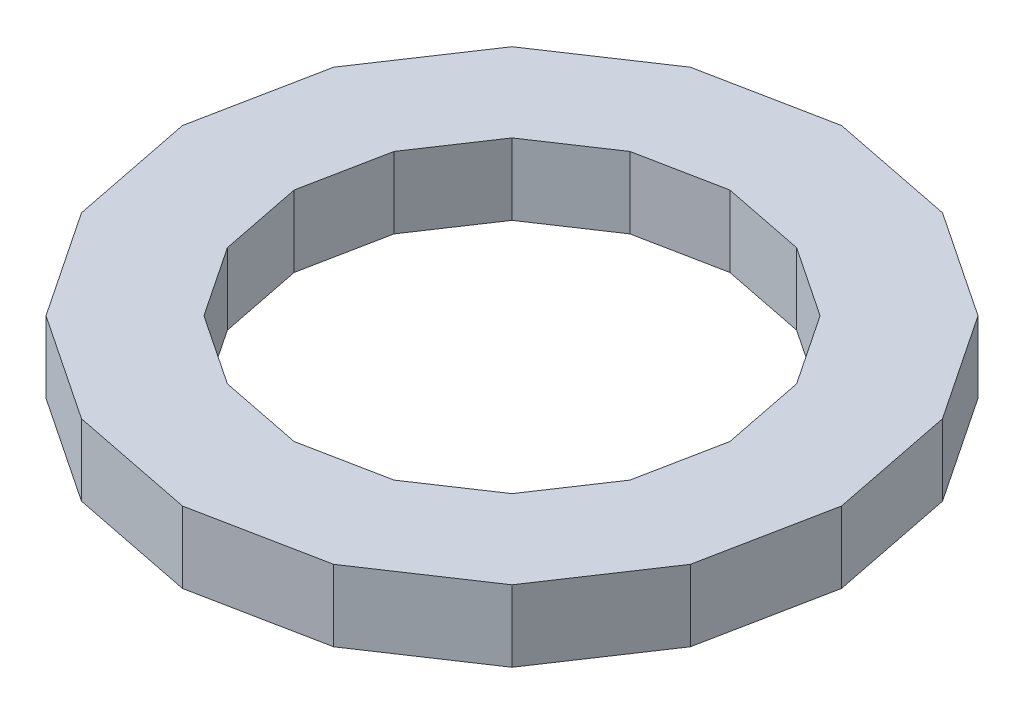
SolidWorks part; units mm, degrees
ref_plane "Front Plane" through (0, 0, 0) normal (0, 0, 1) x (1, 0, 0)
ref_plane "Top Plane" through (0, 0, 0) normal (0, 1, 0) x (1, 0, 0)
ref_plane "Right Plane" through (0, 0, 0) normal (1, 0, 0) x (0, 0, -1)
sketch "Sketch1" plane through (0, 0, 0) normal (0, 1, 0) x (1, 0, 0)
  line L1 (58.1001, 0) -> (53.6775, 22.234)
  line L2 (53.6775, 22.234) -> (41.083, 41.083)
  line L3 (41.083, 41.083) -> (22.234, 53.6775)
  line L4 (22.234, 53.6775) -> (0, 58.1001)
  line L5 (0, 58.1001) -> (-22.234, 53.6775)
  line L6 (-22.234, 53.6775) -> (-41.083, 41.083)
  line L7 (-41.083, 41.083) -> (-53.6775, 22.234)
  line L8 (-53.6775, 22.234) -> (-58.1001, 0)
  line L9 (-58.1001, 0) -> (-53.6775, -22.234)
  line L10 (-53.6775, -22.234) -> (-41.083, -41.083)
  line L11 (-41.083, -41.083) -> (-22.234, -53.6775)
  line L12 (-22.234, -53.6775) -> (0, -58.1001)
  line L13 (0, -58.1001) -> (22.234, -53.6775)
  line L14 (22.234, -53.6775) -> (41.083, -41.083)
  line L15 (41.083, -41.083) -> (53.6775, -22.234)
  line L16 (53.6775, -22.234) -> (58.1001, 0)
  line L17 (87.8824, 0) -> (81.1927, 33.6311)
  line L18 (81.1927, 33.6311) -> (62.1422, 62.1422)
  line L19 (62.1422, 62.1422) -> (33.6311, 81.1927)
  line L20 (33.6311, 81.1927) -> (0, 87.8824)
  line L21 (0, 87.8824) -> (-33.6311, 81.1927)
  line L22 (-33.6311, 81.1927) -> (-62.1422, 62.1422)
  line L23 (-62.1422, 62.1422) -> (-81.1927, 33.6311)
  line L24 (-81.1927, 33.6311) -> (-87.8824, 0)
  line L25 (-87.8824, 0) -> (-81.1927, -33.6311)
  line L26 (-81.1927, -33.6311) -> (-62.1422, -62.1422)
  line L27 (-62.1422, -62.1422) -> (-33.6311, -81.1927)
  line L28 (-33.6311, -81.1927) -> (0, -87.8824)
  line L29 (0, -87.8824) -> (33.6311, -81.1927)
  line L30 (33.6311, -81.1927) -> (62.1422, -62.1422)
  line L31 (62.1422, -62.1422) -> (81.1927, -33.6311)
  line L32 (81.1927, -33.6311) -> (87.8824, 0)
  circle A1 centre (0, 0) radius 56.9837 construction
  circle A2 centre (0, 0) radius 86.1937 construction
  dimension "D1" = 29.21
  dimension "D2" = 34.29
extrude "Boss-Extrude1" add sketch "Sketch1" along normal blind 19.05
